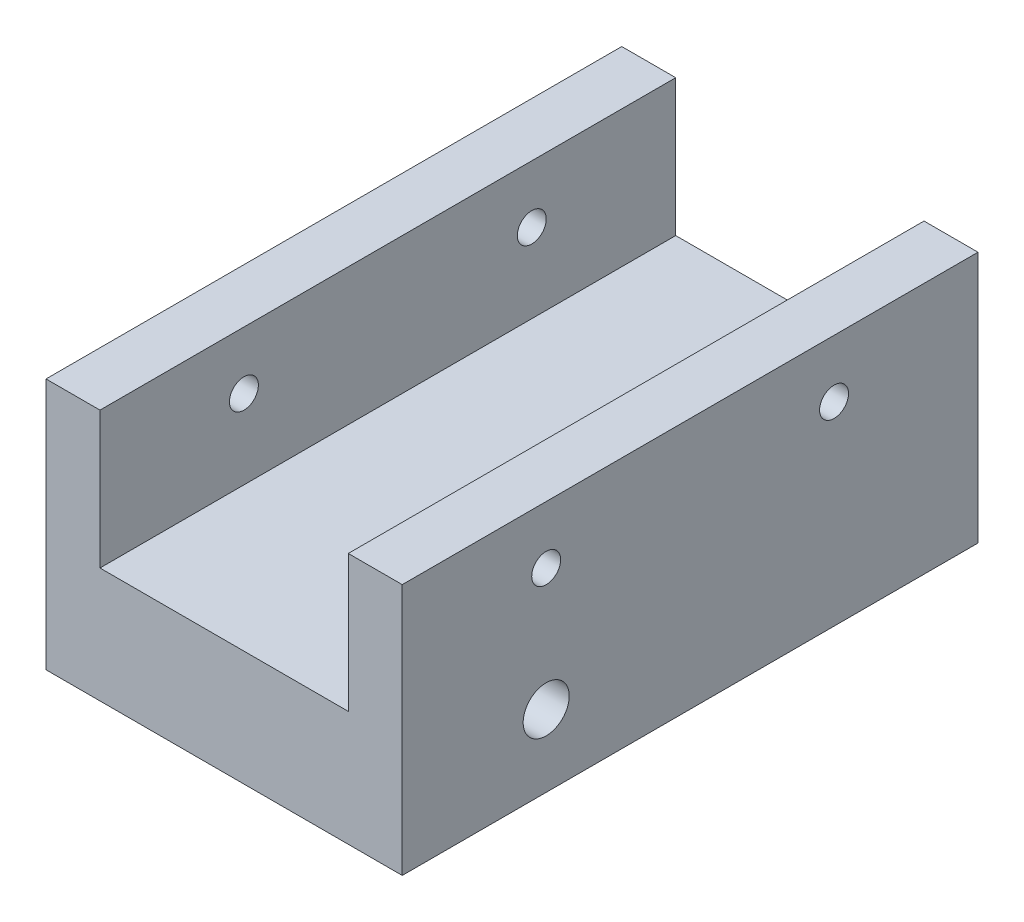
SolidWorks part; units mm, degrees
ref_plane "Front Plane" through (0, 0, 0) normal (0, 0, 1) x (1, 0, 0)
ref_plane "Top Plane" through (0, 0, 0) normal (0, 1, 0) x (1, 0, 0)
ref_plane "Right Plane" through (0, 0, 0) normal (1, 0, 0) x (0, 0, -1)
sketch "Sketch1" plane through (0, 0, 0) normal (0, 0, 1) x (1, 0, 0)
  line L0 (0, 0) -> (62.865, 0)
  line L1 (62.865, 0) -> (62.865, 44.45)
  line L2 (62.865, 44.45) -> (53.34, 44.45)
  line L5 (53.34, 44.45) -> (53.34, 20.32)
  line L6 (53.34, 20.32) -> (9.525, 20.32)
  line L10 (9.525, 44.45) -> (0, 44.45)
  line L11 (0, 44.45) -> (0, 0)
  line L12 (9.525, 44.45) -> (9.525, 20.32)
  point P5 (31.4325, 20.32)
  point P6 (31.4325, 0)
  dimension "D1" = 43.815
  dimension "D2" = 9.525
  dimension "D3" = 24.13
  dimension "D4" = 44.45
extrude "Boss-Extrude1" add sketch "Sketch1" along normal blind 101.6
hole_wizard "#7 (0.201) Diameter Hole1" positions "Sketch6" profile "Sketch7" hole size "#7" standard "ANSI Inch" end condition through all
sketch "Sketch6" plane through (0, 0, 0) normal (-1, 0, 0) x (0, 0, 1)
  line L0 (101.6, 44.45) -> (0, 44.45) construction
  line L1 (101.6, 44.45) -> (101.6, 0) construction
  point P0 (25.4, 34.29)
  point P2 (76.2, 34.29)
  dimension "D1" = 10.16
  dimension "D2" = 50.8
  dimension "D3" = 25.4
sketch "Sketch7" plane through (0, 34.29, 25.4) normal (0, 1, 0) x (0, 0, 1)
  line L0 (0, 0) -> (0, 62.865)
  line L1 (0, 62.865) -> (2.5527, 62.865)
  line L2 (2.5527, 62.865) -> (2.5527, 0)
  line L5 (2.5527, 0) -> (0, 0)
  line L11 (0, -6.35) -> (0, 107.95) construction
  dimension "Thru Hole Dia." = 5.1054
  dimension "Thru Hole Depth" = 62.865
sketch "Sketch5" plane through (0, 0, 0) normal (-1, 0, 0) x (0, 0, 1)
  line L0 (101.6, 44.45) -> (0, 44.45) construction
  line L1 (101.6, 44.45) -> (101.6, 0) construction
  circle A0 centre (76.2, 12.7) radius 4.064
  dimension "D1" = 31.75
  dimension "D3" = 8.128
  dimension "D2" = 25.4
extrude "Cut-Extrude2" cut sketch "Sketch5" against normal through all
sketch "Sketch9" plane through (0, 0, 0) normal (0, 0, -1) x (-1, 0, 0)
  line L0 (-62.865, 44.45) -> (-53.34, 44.45) construction
  line L1 (-53.34, 20.32) -> (-9.525, 20.32) construction
  circle A0 centre (-31.4325, 12.7) radius 3.81
  point P7 (-31.4325, 20.32)
  dimension "D1" = 31.75
  dimension "D2" = 7.62
extrude "Cut-Extrude3" cut sketch "Sketch9" against normal blind 38.1 contours A0
